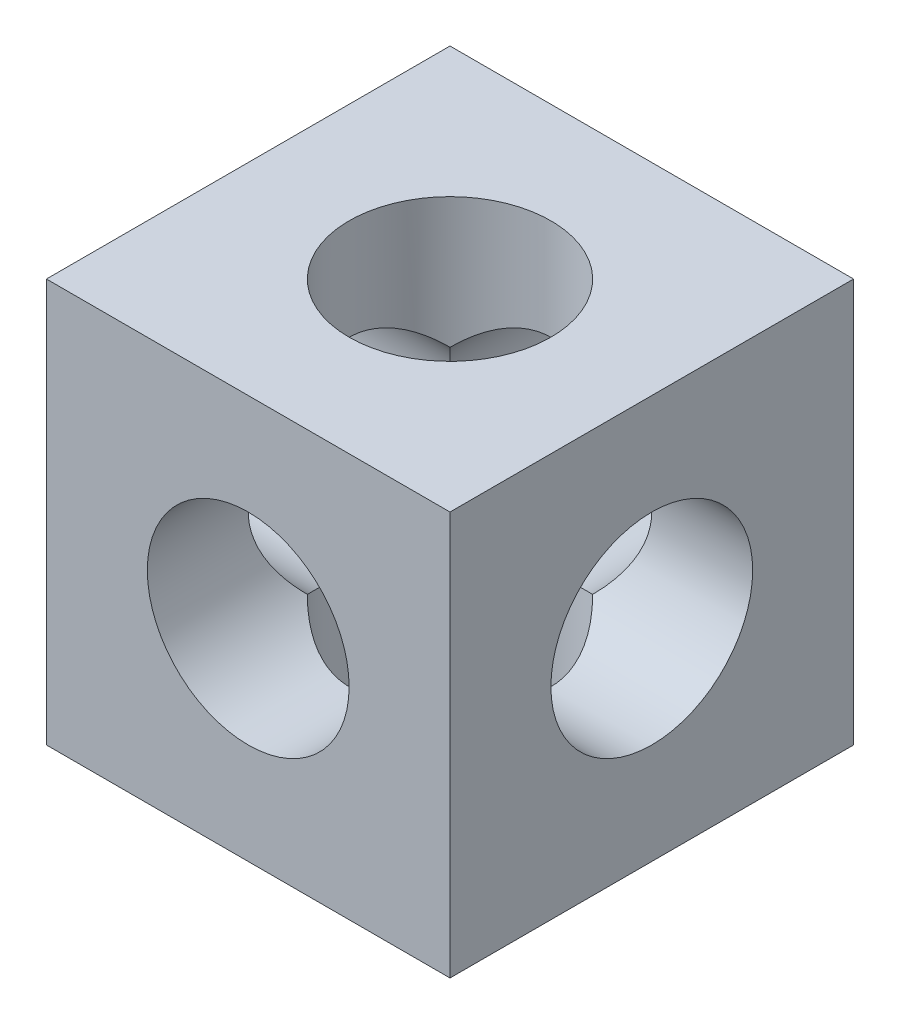
SolidWorks part; units mm, degrees
ref_plane "前视基准面" through (0, 0, 0) normal (0, 0, 1) x (1, 0, 0)
ref_plane "上视基准面" through (0, 0, 0) normal (0, 1, 0) x (1, 0, 0)
ref_plane "右视基准面" through (0, 0, 0) normal (1, 0, 0) x (0, 0, -1)
other "Configuration Table"
sketch "草图1" plane through (0, 0, 0) normal (0, 1, 0) x (1, 0, 0)
  line L0 (3, 0) -> (3, 6) construction
  line L1 (0, 0) -> (6, 0)
  line L2 (0, 0) -> (0, 6)
  line L3 (0, 6) -> (6, 6)
  line L4 (6, 0) -> (6, 6)
  line L6 (0, 3) -> (6, 3) construction
  circle A0 centre (3, 3) radius 1.5
  dimension "D3" = 3
  dimension "D1" = 6
  dimension "D2" = 6
extrude "凸台-拉伸1" add sketch "草图1" along normal blind 6
sketch "草图2" plane through (0, 0, 0) normal (0, 0, 1) x (1, 0, 0)
  line L0 (3, 0) -> (3, 6) construction
  line L1 (0, 0) -> (6, 0) construction
  line L2 (0, 6) -> (6, 6) construction
  line L3 (0, 3) -> (6, 3) construction
  line L4 (0, 6) -> (0, 0) construction
  line L5 (6, 6) -> (6, 0) construction
  circle A0 centre (3, 3) radius 1.5
  dimension "D1" = 3
extrude "切除-拉伸1" cut sketch "草图2" against normal blind 6 contours A0
sketch "草图3" plane through (6, 0, 0) normal (1, 0, 0) x (0, 0, -1)
  line L0 (3, 0) -> (3, 6) construction
  line L1 (0, 0) -> (6, 0) construction
  line L2 (0, 6) -> (6, 6) construction
  line L4 (0, 6) -> (0, 0) construction
  line L5 (0, 3) -> (6, 3) construction
  line L6 (6, 6) -> (6, 0) construction
  circle A0 centre (3, 3) radius 1.5
  dimension "D1" = 3
extrude "切除-拉伸2" cut sketch "草图3" against normal blind 6 contours A0
